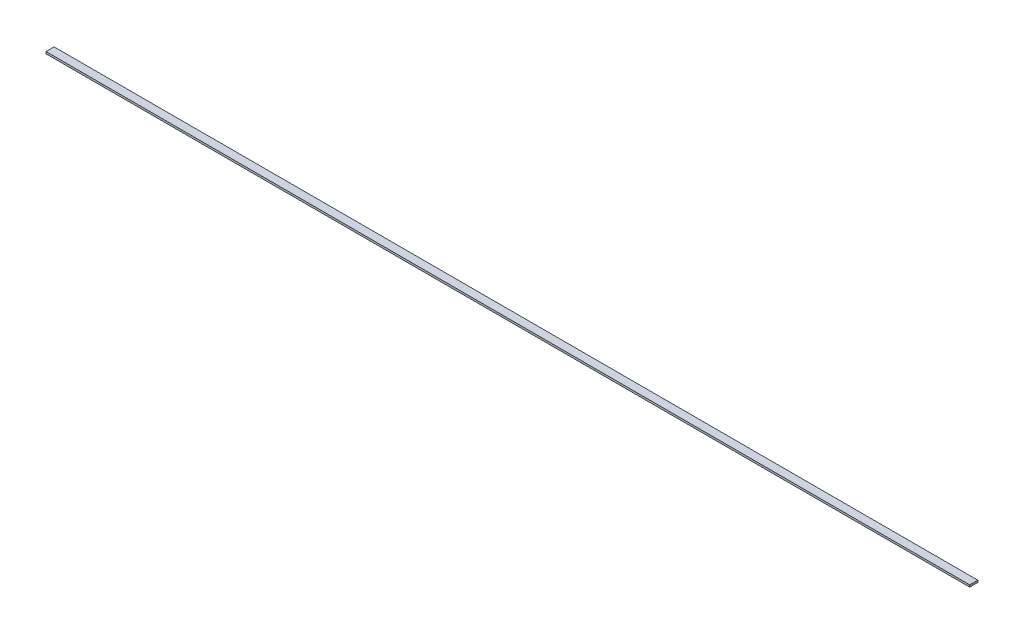
SolidWorks part; units mm, degrees
material "Manual Density from Real Component Bordo attacco e uscita"
ref_plane "Piano frontale" through (0, 0, 0) normal (0, 0, 1) x (1, 0, 0)
ref_plane "Piano superiore" through (0, 0, 0) normal (0, 1, 0) x (1, 0, 0)
ref_plane "Piano destro" through (0, 0, 0) normal (1, 0, 0) x (0, 0, -1)
curve "Curva1"
  spline degree 3 poles (0, 0.1724, 248.285) (0, -0.053, 250.4273) (0, 0.2462, 248.3284) (0, 0.5529, 246.6445) (0, 1.2459, 242.6221) (0, 2.0989, 237.7464) (0, 3.1818, 231.3634) (0, 4.2933, 223.9772) (0, 5.7312, 215.5604) (0, 7.1315, 206.3004) (0, 8.6324, 196.1631) (0, 10.1162, 185.3524) (0, 11.5493, 173.9891) (0, 12.8816, 162.1914) (0, 14.0593, 150.0724) (0, 15.0523, 137.7438) (0, 15.8256, 125.3116) (0, 16.3834, 112.8888) (0, 16.7267, 100.597) (0, 16.8648, 88.5669) (0, 16.792, 76.9314) (0, 16.4941, 65.8165) (0, 15.9609, 55.3329) (0, 15.1594, 45.573) (0, 14.0978, 36.6074) (0, 12.7884, 28.4972) (0, 11.2839, 21.2988) (0, 9.6413, 15.0749) (0, 7.9136, 9.8809) (0, 6.1182, 5.7699) (0, 4.2384, 2.7289) (0, 2.3057, 0.8126) (0, 0.7927, 0.0312) (0, -0.4105, -0.0213) (0, -1.7115, 0.4949) (0, -2.8658, 2.6253) (0, -4.0404, 5.6977) (0, -4.9287, 10.0719) (0, -5.5974, 15.6262) (0, -6.0122, 22.4122) (0, -6.265, 30.3619) (0, -6.3814, 39.3972) (0, -6.3554, 49.3987) (0, -6.2185, 60.2453) (0, -5.9476, 71.8018) (0, -5.5368, 83.9408) (0, -4.9386, 96.5461) (0, -4.1527, 109.5201) (0, -3.2196, 122.7671) (0, -2.1909, 136.1764) (0, -1.148, 149.6158) (0, -0.1602, 162.9314) (0, 0.706, 175.9537) (0, 1.3896, 188.4999) (0, 1.8332, 200.3712) (0, 1.9676, 211.3376) (0, 1.8232, 221.1842) (0, 1.4973, 229.6804) (0, 1.0741, 236.8065) (0, 0.6857, 242.1894) (0, 0.3087, 246.5181) (0, 0.1724, 248.285) (0, -0.053, 250.4273) (0, 0.2462, 248.3284) knots -0.014202 -0.006329 -0.001589 0 0.001576 0.006211 0.01368 0.023764 0.036307 0.051658 0.068045 0.086769 0.107053 0.128647 0.151303 0.174786 0.19886 0.223309 0.247929 0.272522 0.296848 0.320648 0.343669 0.365658 0.3864 0.405741 0.423561 0.439779 0.454311 0.467034 0.477831 0.486643 0.493542 0.498786 0.50271 0.50309 0.505896 0.510322 0.516831 0.525521 0.536535 0.549945 0.565696 0.583577 0.603379 0.624844 0.647727 0.671743 0.696673 0.722357 0.748609 0.77521 0.801891 0.828329 0.854175 0.879074 0.902636 0.924421 0.943939 0.960827 0.974827 0.985798 0.993671 0.998411 1 1.001576 1.006211 1.01368 periodic
sketch "Schizzo1" plane through (0, 0, 0) normal (1, 0, 0) x (0, 0, -1)
  line L0 (-250, 0) -> (0.0001, 0.0174) construction
  line L1 (0.0001, 0.0174) -> (-0.0034, 50.0174) construction
  line L2 (-62.4999, 16.3096) -> (-62.4999, -6.155) construction
  line L4 (-78.4999, 10.0773) -> (-93.4999, 10.0773)
  line L5 (-78.4999, 10.0773) -> (-78.4999, 0.0773)
  line L6 (-78.4999, 0.0773) -> (-93.4999, 0.0773)
  line L7 (-93.4999, 10.0773) -> (-93.4999, 0.0773)
  circle A0 centre (-62.4999, 5.0773) radius 8
  spline S0 degree 3 poles (-248.3284, 0.2462) (-250.4273, -0.053) (-248.285, 0.1724) (-246.5181, 0.3087) (-242.1894, 0.6857) (-236.8065, 1.0741) (-229.6804, 1.4973) (-221.1842, 1.8232) (-211.3376, 1.9676) (-200.3712, 1.8332) (-188.4999, 1.3896) (-175.9537, 0.706) (-162.9314, -0.1602) (-149.6158, -1.148) (-136.1764, -2.1909) (-122.7671, -3.2196) (-109.5201, -4.1527) (-96.5461, -4.9386) (-83.9408, -5.5368) (-71.8018, -5.9476) (-60.2453, -6.2185) (-49.3987, -6.3554) (-39.3972, -6.3814) (-30.3619, -6.265) (-22.4122, -6.0122) (-15.6262, -5.5974) (-10.0719, -4.9287) (-5.6977, -4.0404) (-2.6253, -2.8658) (-0.4949, -1.7115) (0.0213, -0.4105) (-0.0312, 0.7927) (-0.8126, 2.3057) (-2.7289, 4.2384) (-5.7699, 6.1182) (-9.8809, 7.9136) (-15.0749, 9.6413) (-21.2988, 11.2839) (-28.4972, 12.7884) (-36.6074, 14.0978) (-45.573, 15.1594) (-55.3329, 15.9609) (-65.8165, 16.4941) (-76.9314, 16.792) (-88.5669, 16.8648) (-100.597, 16.7267) (-112.8888, 16.3834) (-125.3116, 15.8256) (-137.7438, 15.0523) (-150.0724, 14.0593) (-162.1914, 12.8816) (-173.9891, 11.5493) (-185.3524, 10.1162) (-196.1631, 8.6324) (-206.3004, 7.1315) (-215.5604, 5.7312) (-223.9772, 4.2933) (-231.3634, 3.1818) (-237.7464, 2.0989) (-242.6221, 1.2459) (-246.6445, 0.5529) (-248.3284, 0.2462) (-250.4273, -0.053) (-248.285, 0.1724) knots -0.01368 -0.006211 -0.001576 0 0.001589 0.006329 0.014202 0.025173 0.039173 0.056061 0.075579 0.097364 0.120926 0.145825 0.171671 0.198109 0.22479 0.251391 0.277643 0.303327 0.328257 0.352273 0.375156 0.396621 0.416423 0.434304 0.450055 0.463465 0.474479 0.483169 0.489678 0.494104 0.49691 0.49729 0.501214 0.506458 0.513357 0.522169 0.532966 0.545689 0.560221 0.576439 0.594259 0.6136 0.634342 0.656331 0.679352 0.703152 0.727478 0.752071 0.776691 0.80114 0.825214 0.848697 0.871353 0.892947 0.913231 0.931955 0.948342 0.963693 0.976236 0.98632 0.993789 0.998424 1 1.001589 1.006329 1.014202 only from (-250, 0) to (-250, 0) construction
  spline S1 degree 3 poles (-248.3284, 0.2462) (-250.4273, -0.053) (-248.285, 0.1724) (-246.5181, 0.3087) (-242.1894, 0.6857) (-236.8065, 1.0741) (-229.6804, 1.4973) (-221.1842, 1.8232) (-211.3376, 1.9676) (-200.3712, 1.8332) (-188.4999, 1.3896) (-175.9537, 0.706) (-162.9314, -0.1602) (-149.6158, -1.148) (-136.1764, -2.1909) (-122.7671, -3.2196) (-109.5201, -4.1527) (-96.5461, -4.9386) (-83.9408, -5.5368) (-71.8018, -5.9476) (-60.2453, -6.2185) (-49.3987, -6.3554) (-39.3972, -6.3814) (-30.3619, -6.265) (-22.4122, -6.0122) (-15.6262, -5.5974) (-10.0719, -4.9287) (-5.6977, -4.0404) (-2.6253, -2.8658) (-0.4949, -1.7115) (0.0213, -0.4105) (-0.0312, 0.7927) (-0.8126, 2.3057) (-2.7289, 4.2384) (-5.7699, 6.1182) (-9.8809, 7.9136) (-15.0749, 9.6413) (-21.2988, 11.2839) (-28.4972, 12.7884) (-36.6074, 14.0978) (-45.573, 15.1594) (-55.3329, 15.9609) (-65.8165, 16.4941) (-76.9314, 16.792) (-88.5669, 16.8648) (-100.597, 16.7267) (-112.8888, 16.3834) (-125.3116, 15.8256) (-137.7438, 15.0523) (-150.0724, 14.0593) (-162.1914, 12.8816) (-173.9891, 11.5493) (-185.3524, 10.1162) (-196.1631, 8.6324) (-206.3004, 7.1315) (-215.5604, 5.7312) (-223.9772, 4.2933) (-231.3634, 3.1818) (-237.7464, 2.0989) (-242.6221, 1.2459) (-246.6445, 0.5529) (-248.3284, 0.2462) (-250.4273, -0.053) (-248.285, 0.1724) knots -0.01368 -0.006211 -0.001576 0 0.001589 0.006329 0.014202 0.025173 0.039173 0.056061 0.075579 0.097364 0.120926 0.145825 0.171671 0.198109 0.22479 0.251391 0.277643 0.303327 0.328257 0.352273 0.375156 0.396621 0.416423 0.434304 0.450055 0.463465 0.474479 0.483169 0.489678 0.494104 0.49691 0.49729 0.501214 0.506458 0.513357 0.522169 0.532966 0.545689 0.560221 0.576439 0.594259 0.6136 0.634342 0.656331 0.679352 0.703152 0.727478 0.752071 0.776691 0.80114 0.825214 0.848697 0.871353 0.892947 0.913231 0.931955 0.948342 0.963693 0.976236 0.98632 0.993789 0.998424 1 1.001589 1.006329 1.014202 only from (-250, 0) to (-250, 0)
  point P11 (-78.4999, 5.0773)
  dimension "D3" = 16
  dimension "D1" = 50
  dimension "D2" = 62.5
  dimension "D4" = 15
  dimension "D5" = 10
  dimension "D6" = 16
extrude "CorpoCentina" add sketch "Schizzo1" along normal blind 5
sketch "Schizzo2" plane through (0, 0, 0) normal (-1, 0, 0) x (0, 0, 1)
  line L0 (10, 7.8782) -> (10, -4.8487)
  spline S0 degree 3 poles (248.285, 0.1724) (250.4273, -0.053) (248.3284, 0.2462) (246.6445, 0.5529) (242.6221, 1.2459) (237.7464, 2.0989) (231.3634, 3.1818) (223.9772, 4.2933) (215.5604, 5.7312) (206.3004, 7.1315) (196.1631, 8.6324) (185.3524, 10.1162) (173.9891, 11.5493) (162.1914, 12.8816) (150.0724, 14.0593) (137.7438, 15.0523) (125.3116, 15.8256) (112.8888, 16.3834) (100.597, 16.7267) (88.5669, 16.8648) (76.9314, 16.792) (65.8165, 16.4941) (55.3329, 15.9609) (45.573, 15.1594) (36.6074, 14.0978) (28.4972, 12.7884) (21.2988, 11.2839) (15.0749, 9.6413) (9.8809, 7.9136) (5.7699, 6.1182) (2.7289, 4.2384) (0.8126, 2.3057) (0.0312, 0.7927) (-0.0213, -0.4105) (0.4949, -1.7115) (2.6253, -2.8658) (5.6977, -4.0404) (10.0719, -4.9287) (15.6262, -5.5974) (22.4122, -6.0122) (30.3619, -6.265) (39.3972, -6.3814) (49.3987, -6.3554) (60.2453, -6.2185) (71.8018, -5.9476) (83.9408, -5.5368) (96.5461, -4.9386) (109.5201, -4.1527) (122.7671, -3.2196) (136.1764, -2.1909) (149.6158, -1.148) (162.9314, -0.1602) (175.9537, 0.706) (188.4999, 1.3896) (200.3712, 1.8332) (211.3376, 1.9676) (221.1842, 1.8232) (229.6804, 1.4973) (236.8065, 1.0741) (242.1894, 0.6857) (246.5181, 0.3087) (248.285, 0.1724) (250.4273, -0.053) (248.3284, 0.2462) knots -0.014202 -0.006329 -0.001589 0 0.001576 0.006211 0.01368 0.023764 0.036307 0.051658 0.068045 0.086769 0.107053 0.128647 0.151303 0.174786 0.19886 0.223309 0.247929 0.272522 0.296848 0.320648 0.343669 0.365658 0.3864 0.405741 0.423561 0.439779 0.454311 0.467034 0.477831 0.486643 0.493542 0.498786 0.50271 0.50309 0.505896 0.510322 0.516831 0.525521 0.536535 0.549945 0.565696 0.583577 0.603379 0.624844 0.647727 0.671743 0.696673 0.722357 0.748609 0.77521 0.801891 0.828329 0.854175 0.879074 0.902636 0.924421 0.943939 0.960827 0.974827 0.985798 0.993671 0.998411 1 1.001576 1.006211 1.01368 only from (250, 0) to (250, 0) construction
  spline S1 degree 3 poles (10, -4.8487) (11.7384, -5.1292) (15.7314, -5.6039) (22.4122, -6.0122) (30.3619, -6.265) (39.3972, -6.3814) (49.3987, -6.3554) (60.2453, -6.2185) (71.8018, -5.9476) (83.9408, -5.5368) (96.5461, -4.9386) (109.5201, -4.1527) (122.7671, -3.2196) (136.1764, -2.1909) (149.6158, -1.148) (162.9314, -0.1602) (175.9537, 0.706) (188.4999, 1.3896) (200.3712, 1.8332) (211.3376, 1.9676) (221.1842, 1.8232) (229.6804, 1.4973) (236.8065, 1.0741) (242.1894, 0.6857) (246.5181, 0.3087) (248.285, 0.1724) (250.4273, -0.053) (248.3284, 0.2462) (246.6445, 0.5529) (242.6221, 1.2459) (237.7464, 2.0989) (231.3634, 3.1818) (223.9772, 4.2933) (215.5604, 5.7312) (206.3004, 7.1315) (196.1631, 8.6324) (185.3524, 10.1162) (173.9891, 11.5493) (162.1914, 12.8816) (150.0724, 14.0593) (137.7438, 15.0523) (125.3116, 15.8256) (112.8888, 16.3834) (100.597, 16.7267) (88.5669, 16.8648) (76.9314, 16.792) (65.8165, 16.4941) (55.3329, 15.9609) (45.573, 15.1594) (36.6074, 14.0978) (28.4972, 12.7884) (21.2988, 11.2839) (15.2148, 9.6782) (11.5714, 8.4756) (10, 7.8782) knots 0.526144 0.526144 0.526144 0.526144 0.536535 0.549945 0.565696 0.583577 0.603379 0.624844 0.647727 0.671743 0.696673 0.722357 0.748609 0.77521 0.801891 0.828329 0.854175 0.879074 0.902636 0.924421 0.943939 0.960827 0.974827 0.985798 0.993671 0.998411 1 1.001576 1.006211 1.01368 1.023764 1.036307 1.051658 1.068045 1.086769 1.107053 1.128647 1.151303 1.174786 1.19886 1.223309 1.247929 1.272522 1.296848 1.320648 1.343669 1.365658 1.3864 1.405741 1.423561 1.439779 1.454311 1.467034 1.476976 1.476976 1.476976 1.476976
  dimension "D1" = 10
extrude "RimozioneRetroCentina" cut sketch "Schizzo2" against normal through all
sketch "Schizzo3" plane through (5, 0, 0) normal (1, 0, 0) x (0, 0, -1)
  line L0 (0, 0) -> (-10, 1.5148) construction
  line L1 (0.0001, 1) -> (-8.1999, 1) construction
  line L2 (0.0001, 1) -> (0.0001, -1) construction
  line L3 (0.0001, -1) -> (-8.1999, -1) construction
  line L4 (-8.1999, 1) -> (-8.1999, -1)
  line L5 (-10, 7.8782) -> (-10, -4.8487) construction
  line L6 (10.0001, 11) -> (10.0001, -11)
  line L7 (10.0001, -11) -> (-18.1999, -11)
  line L8 (-18.1999, 11) -> (-18.1999, -11)
  line L9 (10.0001, 11) -> (-18.1999, 11)
  line L10 (-8.1999, 1) -> (-0.2015, 1)
  line L11 (-8.1999, -1) -> (-0.2665, -1)
  spline S0 degree 3 poles (-248.3284, 0.2462) (-250.4273, -0.053) (-248.285, 0.1724) (-246.5181, 0.3087) (-242.1894, 0.6857) (-236.8065, 1.0741) (-229.6804, 1.4973) (-221.1842, 1.8232) (-211.3376, 1.9676) (-200.3712, 1.8332) (-188.4999, 1.3896) (-175.9537, 0.706) (-162.9314, -0.1602) (-149.6158, -1.148) (-136.1764, -2.1909) (-122.7671, -3.2196) (-109.5201, -4.1527) (-96.5461, -4.9386) (-83.9408, -5.5368) (-71.8018, -5.9476) (-60.2453, -6.2185) (-49.3987, -6.3554) (-39.3972, -6.3814) (-30.3619, -6.265) (-22.4122, -6.0122) (-15.6262, -5.5974) (-10.0719, -4.9287) (-5.6977, -4.0404) (-2.6253, -2.8658) (-0.4949, -1.7115) (0.0213, -0.4105) (-0.0312, 0.7927) (-0.8126, 2.3057) (-2.7289, 4.2384) (-5.7699, 6.1182) (-9.8809, 7.9136) (-15.0749, 9.6413) (-21.2988, 11.2839) (-28.4972, 12.7884) (-36.6074, 14.0978) (-45.573, 15.1594) (-55.3329, 15.9609) (-65.8165, 16.4941) (-76.9314, 16.792) (-88.5669, 16.8648) (-100.597, 16.7267) (-112.8888, 16.3834) (-125.3116, 15.8256) (-137.7438, 15.0523) (-150.0724, 14.0593) (-162.1914, 12.8816) (-173.9891, 11.5493) (-185.3524, 10.1162) (-196.1631, 8.6324) (-206.3004, 7.1315) (-215.5604, 5.7312) (-223.9772, 4.2933) (-231.3634, 3.1818) (-237.7464, 2.0989) (-242.6221, 1.2459) (-246.6445, 0.5529) (-248.3284, 0.2462) (-250.4273, -0.053) (-248.285, 0.1724) knots -0.01368 -0.006211 -0.001576 0 0.001589 0.006329 0.014202 0.025173 0.039173 0.056061 0.075579 0.097364 0.120926 0.145825 0.171671 0.198109 0.22479 0.251391 0.277643 0.303327 0.328257 0.352273 0.375156 0.396621 0.416423 0.434304 0.450055 0.463465 0.474479 0.483169 0.489678 0.494104 0.49691 0.49729 0.501214 0.506458 0.513357 0.522169 0.532966 0.545689 0.560221 0.576439 0.594259 0.6136 0.634342 0.656331 0.679352 0.703152 0.727478 0.752071 0.776691 0.80114 0.825214 0.848697 0.871353 0.892947 0.913231 0.931955 0.948342 0.963693 0.976236 0.98632 0.993789 0.998424 1 1.001589 1.006329 1.014202 only from (-10, -4.8487) to (-10, 7.8782) construction
  spline S1 degree 3 poles (-0.2665, -1) (-0.1035, -0.6893) (0.0156, -0.2788) (-0.0143, 0.4067) (-0.1001, 0.7388) (-0.2015, 1) knots 0.494882 0.494882 0.494882 0.494882 0.49691 0.49729 0.498933 0.498933 0.498933 0.498933
  point P11 (0.0001, 0)
  dimension "D1" = 2
  dimension "D2" = 8.2
  dimension "D3" = 10
extrude "TaglioListello" cut sketch "Schizzo3" against normal through all
sketch "Schizzo4" plane through (5, 0, 0) normal (1, 0, 0) x (0, 0, -1)
  line L3 (-8.1999, -1) -> (-0.2665, -1)
  line L4 (-0.2015, 1) -> (-8.1999, 1)
  line L5 (-8.1999, 1) -> (-8.1999, -1)
  line L6 (-8.1999, -1) -> (-0.2665, -1)
  line L7 (-0.2015, 1) -> (-8.1999, 1)
  line L8 (-8.1999, 1) -> (-8.1999, -1)
  spline S1 degree 3 poles (1165.4321, 1622.8421) (-122.4301, -27.1863) (0.5317, -12.1104) (-0.6607, 15.2239) (-140.1755, 10.3497) (1974.4542, -316.1967) knots 0.424959 0.424959 0.424959 0.424959 0.49691 0.49729 0.5865 0.5865 0.5865 0.5865 only from (-0.2665, -1) to (-0.2015, 1)
  spline S2 degree 3 poles (-0.2665, -1) (-0.1035, -0.6893) (0.0156, -0.2788) (-0.0143, 0.4067) (-0.1001, 0.7388) (-0.2015, 1) knots 0.494882 0.494882 0.494882 0.494882 0.49691 0.49729 0.498933 0.498933 0.498933 0.498933
  dimension "D1" = 0
extrude "EstrusioneListello" add sketch "Schizzo4" along normal blind 910
